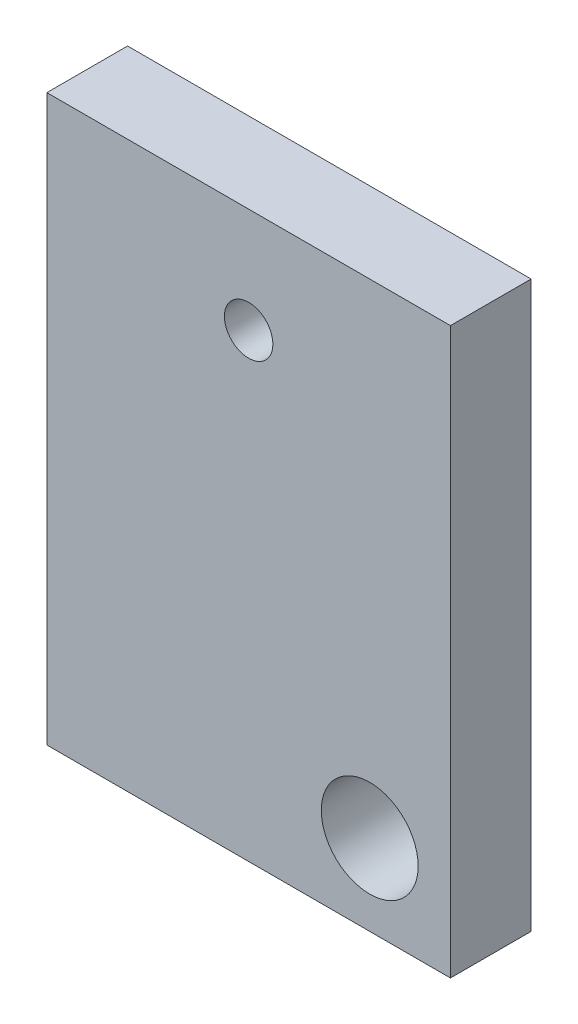
SolidWorks part; units mm, degrees
ref_plane "Front Plane" through (0, 0, 0) normal (0, 0, 1) x (1, 0, 0)
ref_plane "Top Plane" through (0, 0, 0) normal (0, 1, 0) x (1, 0, 0)
ref_plane "Right Plane" through (0, 0, 0) normal (1, 0, 0) x (0, 0, -1)
sketch "Sketch2" plane through (0, 0, 0) normal (0, 0, 1) x (1, 0, 0)
  line L1 (-12.5, -17.5) -> (12.5, -17.5)
  line L2 (-12.5, -17.5) -> (-12.5, 17.5)
  line L3 (-12.5, 17.5) -> (12.5, 17.5)
  line L4 (12.5, -17.5) -> (12.5, 17.5)
  line L5 (-12.5, -17.5) -> (12.5, 17.5) construction
  line L6 (-12.5, 17.5) -> (12.5, -17.5) construction
  point P0 (0, 0)
  dimension "D1" = 25
  dimension "D2" = 35
extrude "Boss-Extrude1" add sketch "Sketch2" along normal blind 5
sketch "Sketch4" plane through (0, 0, 5) normal (0, 0, 1) x (1, 0, 0)
  line L0 (0, -17.5) -> (0, -7.5) construction
  line L1 (-12.5, -17.5) -> (12.5, -17.5) construction
  line L2 (0, -7.5) -> (0, 11) construction
  circle A0 centre (0, 11) radius 1.5
  dimension "D3" = 3
  dimension "D1" = 10
  dimension "D2" = 18.5
extrude "Cut-Extrude1" cut sketch "Sketch4" against normal through all
sketch "Sketch6" plane through (0, 0, 5) normal (0, 0, 1) x (1, 0, 0)
  line L0 (12.5, -17.5) -> (12.5, -7.5) construction
  line L2 (12.5, -17.5) -> (12.5, 17.5) construction
  line L3 (12.5, -12.5) -> (7.5, -12.5) construction
  circle A0 centre (7.5, -12.5) radius 3
  dimension "D2" = 6
  dimension "D1" = 10
  dimension "5" = 5
extrude "Cut-Extrude2" cut sketch "Sketch6" against normal through all
